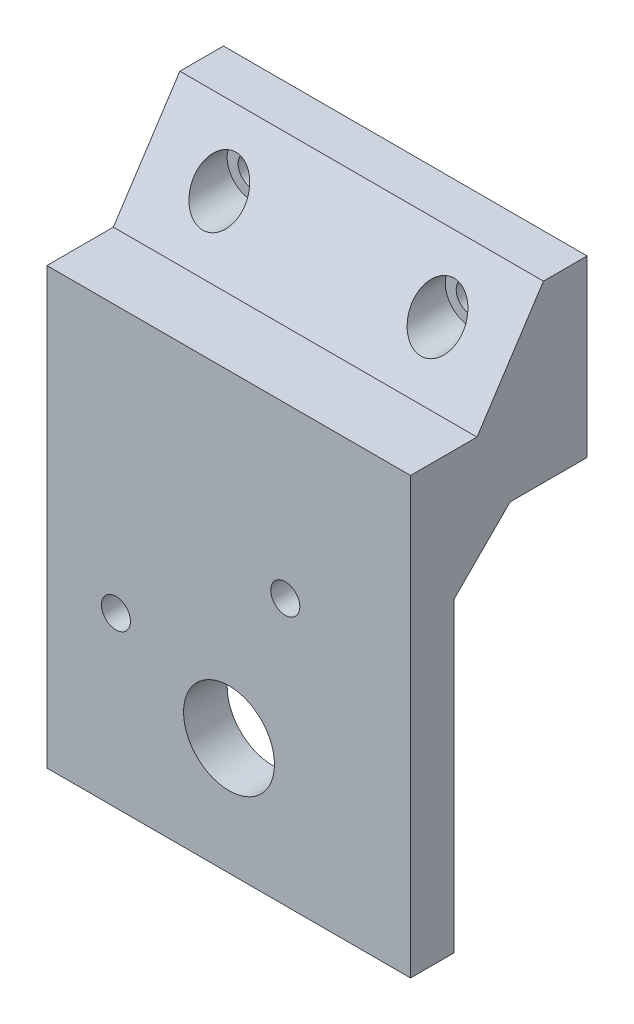
SolidWorks part; units mm, degrees
material "ABS"
ref_plane "Front Plane" through (0, 0, 0) normal (0, 0, 1) x (1, 0, 0)
ref_plane "Top Plane" through (0, 0, 0) normal (0, 1, 0) x (1, 0, 0)
ref_plane "Right Plane" through (0, 0, 0) normal (1, 0, 0) x (0, 0, -1)
sketch "Sketch1" plane through (0, 0, 0) normal (0, 0, 1) x (1, 0, 0)
  line L1 (-37.3941, 10.9555) -> (12.6059, 10.9555)
  line L2 (-37.3941, 10.9555) -> (-37.3941, -7.0445)
  line L3 (-37.3941, -7.0445) -> (12.6059, -7.0445)
  line L4 (12.6059, 10.9555) -> (12.6059, -7.0445)
  dimension "D1" = 50
  dimension "D2" = 18
extrude "Boss-Extrude1" add sketch "Sketch1" along normal blind 7
sketch "Sketch2" plane through (0, 0, 7) normal (0, 0, 1) x (1, 0, 0)
  line L0 (12.6059, -7.0445) -> (12.6059, 10.9555) construction
  line L1 (-37.3941, 10.9555) -> (12.6059, 10.9555)
  line L2 (-37.3941, 10.9555) -> (-37.3941, 2.9555)
  line L3 (-37.3941, 2.9555) -> (12.6059, 2.9555)
  line L4 (12.6059, 10.9555) -> (12.6059, 2.9555)
  dimension "D1" = 8
extrude "Boss-Extrude2" add sketch "Sketch2" along normal blind 6.7
sketch "Sketch3" plane through (12.6059, 0, 0) normal (1, 0, 0) x (0, 0, -1)
  line L0 (-13.7, 10.9555) -> (0, 10.9555) construction
  line L1 (-7, 2.9555) -> (0, 2.9555)
  line L2 (-7, 2.9555) -> (-7, 10.9555)
  line L3 (-7, 10.9555) -> (0, 10.9555)
  line L4 (0, 2.9555) -> (0, 10.9555)
extrude "Boss-Extrude3" add sketch "Sketch3" along normal blind 23
sketch "Sketch4" plane through (-37.3941, 0, 0) normal (-1, 0, 0) x (0, 0, 1)
  line L1 (7, 2.9555) -> (0, 2.9555)
  line L2 (7, 2.9555) -> (7, 10.9555)
  line L3 (7, 10.9555) -> (0, 10.9555)
  line L4 (0, 2.9555) -> (0, 10.9555)
extrude "Boss-Extrude4" add sketch "Sketch4" along normal blind 14
sketch "Sketch5" plane through (0, 0, 7) normal (0, 0, 1) x (1, 0, 0)
  line L1 (-37.3941, -7.0445) -> (12.6059, -7.0445)
  line L2 (-37.3941, -7.0445) -> (-37.3941, 2.9555)
  line L3 (-37.3941, 2.9555) -> (12.6059, 2.9555)
  line L4 (12.6059, -7.0445) -> (12.6059, 2.9555)
extrude "Cut-Extrude1" cut sketch "Sketch5" against normal blind 14
sketch "Sketch6" plane through (0, 0, 7) normal (0, 0, 1) x (1, 0, 0)
  line L0 (35.6059, 10.9555) -> (35.6059, 2.9555) construction
  line L2 (-51.3941, 2.9555) -> (-37.3941, 2.9555) construction
  line L3 (35.6059, 2.9555) -> (12.6059, 2.9555) construction
  circle A0 centre (19.6059, 6.9555) radius 2
  circle A1 centre (28.6059, 6.9555) radius 2
  dimension "D1" = 4
  dimension "D2" = 4
  dimension "D3" = 7
  dimension "D4" = 9
  dimension "D5" = 4
  dimension "D6" = 4
extrude "Cut-Extrude2" cut sketch "Sketch6" against normal blind 14
sketch "Sketch7" plane through (0, 2.9555, 0) normal (0, -1, 0) x (1, 0, 0)
  line L0 (12.6059, 13.7) -> (12.6059, 7) construction
  line L1 (-37.3941, 13.7) -> (12.6059, 13.7)
  line L2 (-37.3941, 13.7) -> (-37.3941, 7.7)
  line L3 (-37.3941, 7.7) -> (12.6059, 7.7)
  line L4 (12.6059, 13.7) -> (12.6059, 7.7)
  dimension "D1" = 6
extrude "Boss-Extrude5" add sketch "Sketch7" along normal blind 67.91
sketch "Sketch8" plane through (0, 0, 13.7) normal (0, 0, 1) x (1, 0, 0)
  line L0 (-12.3941, -44.3312) -> (-12.3941, -64.9545) construction
  line L1 (12.6059, -64.9545) -> (-37.3941, -64.9545) construction
  line L2 (-4.3941, -44.3312) -> (-4.3941, -64.9545)
  line L3 (-20.3941, -44.3312) -> (-20.3941, -64.9545)
  line L4 (-37.3941, 10.9555) -> (-37.3941, -64.9545) construction
  arc A0 (-4.3941, -44.3312) -> (-20.3941, -44.3312) centre (-12.3941, -44.3312) ccw
  arc A1 (-20.3941, -64.9545) -> (-4.3941, -64.9545) centre (-12.3941, -64.9545) ccw
  point P4 (-12.3941, -54.6428)
  dimension "D3" = 20.6233
  dimension "D1" = 16
  dimension "D2" = 25
extrude "Cut-Extrude3" cut sketch "Sketch8" against normal blind 35
sketch "Sketch9" plane through (0, 0, 7.7) normal (0, 0, -1) x (-1, 0, 0)
  line L0 (-12.6059, -64.9545) -> (4.3941, -64.9545) construction
  line L1 (20.3941, -64.9545) -> (37.3941, -64.9545) construction
  circle A0 centre (27.901, -41.7569) radius 2
  circle A1 centre (4.6167, -28.3707) radius 2
  dimension "D1" = 4
  dimension "D2" = 4
  dimension "D3" = 36.5838
  dimension "D4" = 23.1976
extrude "Cut-Extrude5" cut sketch "Sketch9" against normal blind 35
sketch "Sketch13" plane through (0, 0, 7) normal (0, 0, 1) x (1, 0, 0)
  line L1 (-51.3941, 10.9555) -> (-37.3941, 10.9555)
  line L2 (-51.3941, 10.9555) -> (-51.3941, 2.9555)
  line L3 (-51.3941, 2.9555) -> (-37.3941, 2.9555)
  line L4 (-37.3941, 10.9555) -> (-37.3941, 2.9555)
extrude "Cut-Extrude6" cut sketch "Sketch13" against normal blind 10
sketch "Sketch14" plane through (-37.3941, 0, 0) normal (-1, 0, 0) x (0, 0, 1)
  line L1 (7.7, 2.9555) -> (0, 2.9555)
  line L2 (7.7, 2.9555) -> (7.7, 10.9555)
  line L3 (7.7, 10.9555) -> (0, 10.9555)
  line L4 (0, 2.9555) -> (0, 10.9555)
extrude "Cut-Extrude7" cut sketch "Sketch14" against normal blind 120
sketch "Sketch15" plane through (0, 0, 7.7) normal (0, 0, -1) x (-1, 0, 0)
  line L0 (-12.6059, -64.9545) -> (-12.6059, 10.9555) construction
  line L1 (37.3941, 10.9555) -> (-12.6059, 10.9555)
  line L2 (37.3941, 10.9555) -> (37.3941, -3.0445)
  line L3 (37.3941, -3.0445) -> (-12.6059, -3.0445)
  line L4 (-12.6059, 10.9555) -> (-12.6059, -3.0445)
  dimension "D1" = 14
extrude "Boss-Extrude6" add sketch "Sketch15" along normal blind 6.4
sketch "Sketch16" plane through (0, 0, 13.7) normal (0, 0, 1) x (1, 0, 0)
  line L0 (-37.3941, 10.9555) -> (-37.3941, -64.9545) construction
  line L1 (12.6059, 10.9555) -> (-37.3941, 10.9555)
  line L2 (12.6059, 10.9555) -> (12.6059, -3.0445)
  line L3 (12.6059, -3.0445) -> (-37.3941, -3.0445)
  line L4 (-37.3941, 10.9555) -> (-37.3941, -3.0445)
  dimension "D1" = 14
extrude "Cut-Extrude8" cut sketch "Sketch16" against normal up to vertex (6 mm away)
sketch "Sketch17" plane through (-37.3941, 0, 0) normal (-1, 0, 0) x (0, 0, 1)
  line L0 (13.7, -3.0445) -> (7.7, -3.0445)
  line L1 (7.7, -3.0445) -> (7.7, 10.9555)
  line L2 (7.7, 10.9555) -> (13.7, -3.0445)
  line L3 (7.7, -3.0445) -> (1.3, -3.0445)
  line L4 (1.3, -3.0445) -> (7.7, -3.0445) construction
  line L5 (1.3, -3.0445) -> (7.7, -14.7804)
  line L6 (7.7, -64.9545) -> (7.7, -3.0445) construction
  line L7 (7.7, -14.7804) -> (7.7, -3.0445)
  line M1 (1.3, -3.0445) -> (7.7, -3.0445)
  line M2 (7.7, -3.0445) -> (7.7, 10.9555)
extrude "Boss-Extrude7" add sketch "Sketch17" against normal blind 50 contours L2 L0 M2 | L5 L7 M1
sketch "Sketch18" plane through (0, 0, 1.3) normal (0, 0, -1) x (-1, 0, 0)
  line L0 (-12.6059, 10.9555) -> (-12.6059, -3.0445) construction
  line L1 (37.3941, 10.9555) -> (-12.6059, 10.9555) construction
  circle A0 centre (-5.6059, 3.9555) radius 2
  circle A1 centre (30.3941, 4.9553) radius 2
  dimension "D1" = 4
  dimension "D2" = 4
  dimension "D3" = 36
  dimension "D4" = 7
  dimension "D5" = 7
extrude "Cut-Extrude9" cut sketch "Sketch18" against normal blind 6.4
sketch "Sketch19" plane through (0, 0, 7.7) normal (0, 0, -1) x (-1, 0, 0)
  circle A0 centre (30.3941, 4.9553) radius 3.5
  circle A1 centre (-5.6059, 3.9555) radius 3.5
  dimension "D1" = 7
  dimension "D2" = 7
extrude "Cut-Extrude10" cut sketch "Sketch19" against normal blind 6.4
sketch "Sketch20" plane through (-37.3941, 0, 0) normal (-1, 0, 0) x (0, 0, 1)
  line L0 (13.7, -3.0445) -> (13.7, -64.9545) construction
  line L1 (1.3, 10.9555) -> (13.7, 10.9555)
  line L2 (1.3, 10.9555) -> (1.3, -15.1123)
  line L3 (1.3, -15.1123) -> (13.7, -15.1123)
  line L4 (13.7, 10.9555) -> (13.7, -15.1123)
extrude "Cut-Extrude11" cut sketch "Sketch20" against normal blind 70
sketch "Sketch21" plane through (0, -15.1123, 0) normal (0, 1, 0) x (1, 0, 0)
  line L1 (12.6059, -13.7) -> (-37.3941, -13.7)
  line L2 (12.6059, -13.7) -> (12.6059, -7.7)
  line L3 (12.6059, -7.7) -> (-37.3941, -7.7)
  line L4 (-37.3941, -13.7) -> (-37.3941, -7.7)
extrude "Boss-Extrude8" add sketch "Sketch21" along normal blind 10
sketch "Sketch22" plane through (0, 0, 7.7) normal (0, 0, -1) x (-1, 0, 0)
  line L1 (37.3941, -5.1123) -> (-12.6059, -5.1123)
  line L2 (37.3941, -5.1123) -> (37.3941, -15.1123)
  line L3 (37.3941, -15.1123) -> (-12.6059, -15.1123)
  line L4 (-12.6059, -5.1123) -> (-12.6059, -15.1123)
  dimension "D1" = 10
extrude "Boss-Extrude9" add sketch "Sketch22" along normal blind 18.28
sketch "Sketch23" plane through (0, -5.1123, 0) normal (0, 1, 0) x (1, 0, 0)
  line L0 (-37.3941, 10.58) -> (-37.3941, -13.7) construction
  line L1 (12.6059, 10.58) -> (-37.3941, 10.58)
  line L2 (12.6059, 10.58) -> (12.6059, 4.58)
  line L3 (12.6059, 4.58) -> (-37.3941, 4.58)
  line L4 (-37.3941, 10.58) -> (-37.3941, 4.58)
  dimension "D1" = 6
extrude "Boss-Extrude10" add sketch "Sketch23" along normal blind 14
sketch "Sketch24" plane through (0, 0, -4.58) normal (0, 0, 1) x (1, 0, 0)
  line L1 (12.6059, 8.8877) -> (12.6059, -5.1123) construction
  line L2 (-37.3941, 8.8877) -> (-37.3941, -5.1123) construction
  line L3 (-37.3941, 8.8877) -> (12.6059, 8.8877) construction
  circle A0 centre (2.6059, 1.8877) radius 2
  circle A1 centre (-27.3941, 1.8877) radius 2
  dimension "D1" = 4
  dimension "D2" = 4
  dimension "D3" = 10
  dimension "D4" = 10
  dimension "D5" = 7
  dimension "D6" = 0
extrude "Cut-Extrude12" cut sketch "Sketch24" against normal blind 14
sketch "Sketch25" plane through (-37.3941, 0, 0) normal (-1, 0, 0) x (0, 0, 1)
  line L0 (7.7, -15.1123) -> (0, -15.1123)
  line L1 (-10.58, -15.1123) -> (7.7, -15.1123) construction
  line L2 (0, -15.1123) -> (7.7, -22.8123)
  line L3 (7.7, -64.9545) -> (7.7, -15.1123) construction
  line L4 (7.7, -22.8123) -> (7.7, -15.1123)
  line L5 (-4.58, -5.1123) -> (4.56, -5.1123)
  line L6 (-4.58, -5.1123) -> (13.7, -5.1123) construction
  line L7 (4.56, -5.1123) -> (-4.58, 8.8877)
  line L8 (-4.58, 8.8877) -> (-4.58, -5.1123)
extrude "Boss-Extrude11" add sketch "Sketch25" against normal up to vertex (50 mm away)
sketch "Sketch26" plane through (0, 0, -4.58) normal (0, 0, -1) x (-1, 0, 0)
  circle A0 centre (27.3941, 1.8877) radius 3.5
  circle A1 centre (-2.6059, 1.8877) radius 3.5
  dimension "D1" = 7
  dimension "D2" = 7
extrude "Cut-Extrude13" cut sketch "Sketch26" against normal blind 14
sketch "Sketch27" plane through (0, 0, 7.7) normal (0, 0, -1) x (-1, 0, 0)
  line L1 (20.3941, -64.9545) -> (3.5776, -64.9545)
  line L2 (20.3941, -64.9545) -> (20.3941, -35.7506)
  line L3 (20.3941, -35.7506) -> (3.5776, -35.7506)
  line L4 (3.5776, -64.9545) -> (3.5776, -35.7506)
extrude "Boss-Extrude12" add sketch "Sketch27" against normal up to vertex (6 mm away)
sketch "Sketch28" plane through (0, 0, 7.7) normal (0, 0, -1) x (-1, 0, 0)
  circle A0 centre (12.3549, -48.8794) radius 6.25
  circle A1 centre (27.901, -41.7569) radius 2 construction
  circle A2 centre (4.6167, -28.3707) radius 2 construction
  dimension "D1" = 12.5
  dimension "D2" = 17.1
  dimension "D3" = 21.92
extrude "Cut-Extrude14" cut sketch "Sketch28" against normal blind 10
